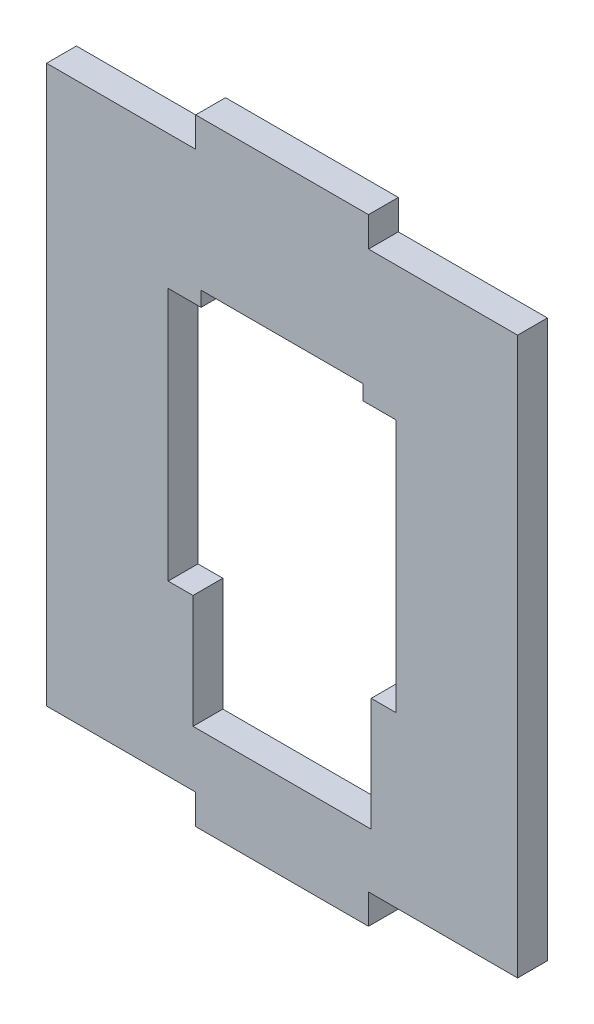
SolidWorks part; units mm, degrees
ref_plane "Přední rovina" through (0, 0, 0) normal (0, 0, 1) x (1, 0, 0)
ref_plane "Horní rovina" through (0, 0, 0) normal (0, 1, 0) x (1, 0, 0)
ref_plane "Pravá rovina" through (0, 0, 0) normal (1, 0, 0) x (0, 0, -1)
sketch "Skica1" plane through (0, 0, 0) normal (0, 0, 1) x (1, 0, 0)
  line L0 (0, 3) -> (15, 3)
  line L1 (15, 0) -> (32.38, 0)
  line L2 (0, 3) -> (0, 59)
  line L4 (47.38, 3) -> (47.38, 59)
  line L5 (15, 3) -> (15, 0)
  line L6 (32.38, 3) -> (32.38, 0)
  line L7 (32.38, 3) -> (47.38, 3)
  line L8 (47.38, 31) -> (-33.6612, 31) construction
  line L9 (32.38, 59) -> (47.38, 59)
  line L10 (32.38, 59) -> (32.38, 62)
  line L11 (15, 62) -> (32.38, 62)
  line L12 (15, 59) -> (15, 62)
  line L13 (0, 59) -> (15, 59)
  line L14 (12.228, 31) -> (12.228, 45.5)
  line L15 (12.228, 45) -> (12.228, 20.5) construction
  line L16 (12.228, 45.5) -> (15.54, 45.5)
  line L17 (15.54, 45.5) -> (15.54, 47)
  line L18 (15.54, 47) -> (31.84, 47)
  line L19 (31.84, 47) -> (31.84, 45.5)
  line L20 (31.84, 45.5) -> (35.152, 45.5)
  line L21 (35.152, 45.5) -> (35.152, 31)
  line L22 (35.152, 20.5) -> (35.152, 45) construction
  line L23 (31.54, 47) -> (28.5912, 47) construction
  line L24 (12.228, 31) -> (12.228, 20)
  line L27 (14.728, 8.6) -> (32.652, 8.6)
  line L29 (28.7708, 18.6) -> (31.3571, 18.6) construction
  line L31 (35.152, 20) -> (35.152, 31)
  line L32 (35.152, 20) -> (32.652, 20)
  line L33 (12.728, 20) -> (34.652, 20) construction
  line L34 (32.652, 20) -> (32.652, 8.6)
  line L35 (12.228, 20) -> (14.728, 20)
  line L36 (14.728, 20) -> (14.728, 8.6)
  point P33 (15.2411, 8.6)
  dimension "D1" = 47.38
  dimension "D2" = 62
  dimension "D3" = 15
  dimension "D4" = 15
  dimension "D5" = 3
  dimension "D6" = 17.38
  dimension "D7" = 3
  dimension "D8" = 0
  dimension "D9" = 10
  dimension "D10" = 2.5
  dimension "D11" = 2.5
  dimension "D12" = 90
  dimension "D13" = 90
extrude "Přidat vysunutím1" add sketch "Skica1" along normal blind 3
